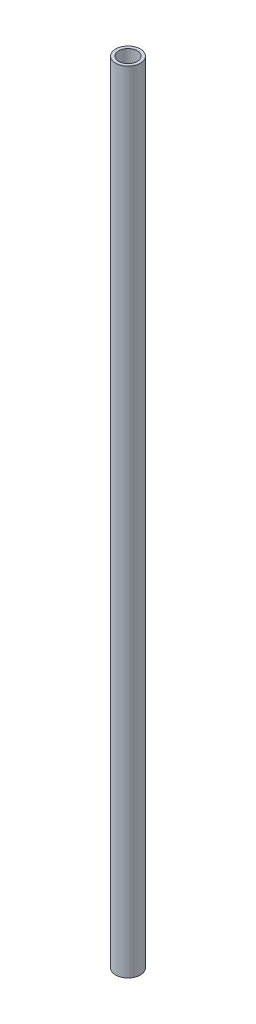
SolidWorks part; units mm, degrees
ref_plane "Front Plane" through (0, 0, 0) normal (0, 0, 1) x (1, 0, 0)
ref_plane "Top Plane" through (0, 0, 0) normal (0, 1, 0) x (1, 0, 0)
ref_plane "Right Plane" through (0, 0, 0) normal (1, 0, 0) x (0, 0, -1)
sketch "Sketch1" plane through (0, 0, 0) normal (0, 1, 0) x (1, 0, 0)
  circle A0 centre (0, 0) radius 1.5875
extrude "Boss-Extrude1" add sketch "Sketch1" along normal blind 101.6
sketch "Sketch2" plane through (0, 101.6, 0) normal (0, 1, 0) x (1, 0, 0)
  circle A0 centre (0, 0) radius 1.1906
extrude "Cut-Extrude1" cut sketch "Sketch2" against normal through all
